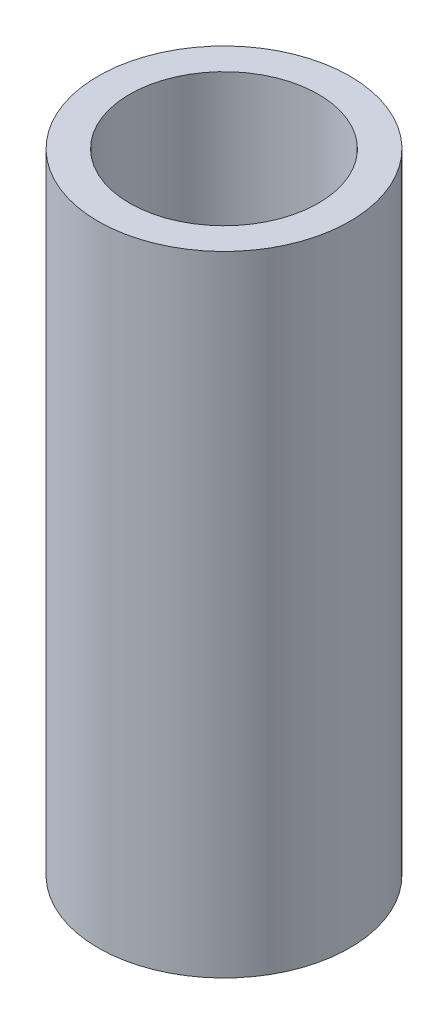
SolidWorks part; units mm, degrees
ref_plane "Front Plane" through (0, 0, 0) normal (0, 0, 1) x (1, 0, 0)
ref_plane "Top Plane" through (0, 0, 0) normal (0, 1, 0) x (1, 0, 0)
ref_plane "Right Plane" through (0, 0, 0) normal (1, 0, 0) x (0, 0, -1)
sketch3d "3DSketch1"
  line L0 (0, 0, 0) -> (0, 50, 0)
  dimension "D1" = 50
other "Pipe 21.3 X 2.3(1)"
ref_plane "Plane1" through (0, 0, 0) normal (0, 1, 0) x (1, 0, 0)
sketch "Sketch12" plane through (0, 0, 0) normal (0, 1, 0) x (1, 0, 0)
  circle A0 centre (0, 0) radius 7.5
  circle A1 centre (0, 0) radius 10
  point P3 (0, 10)
  point P5 (-10, 0)
  point P6 (0, -10)
  point P7 (10, 0)
  point P8 (0, 0)
  dimension "In_dia" = 15
  dimension "Out_dia" = 20
